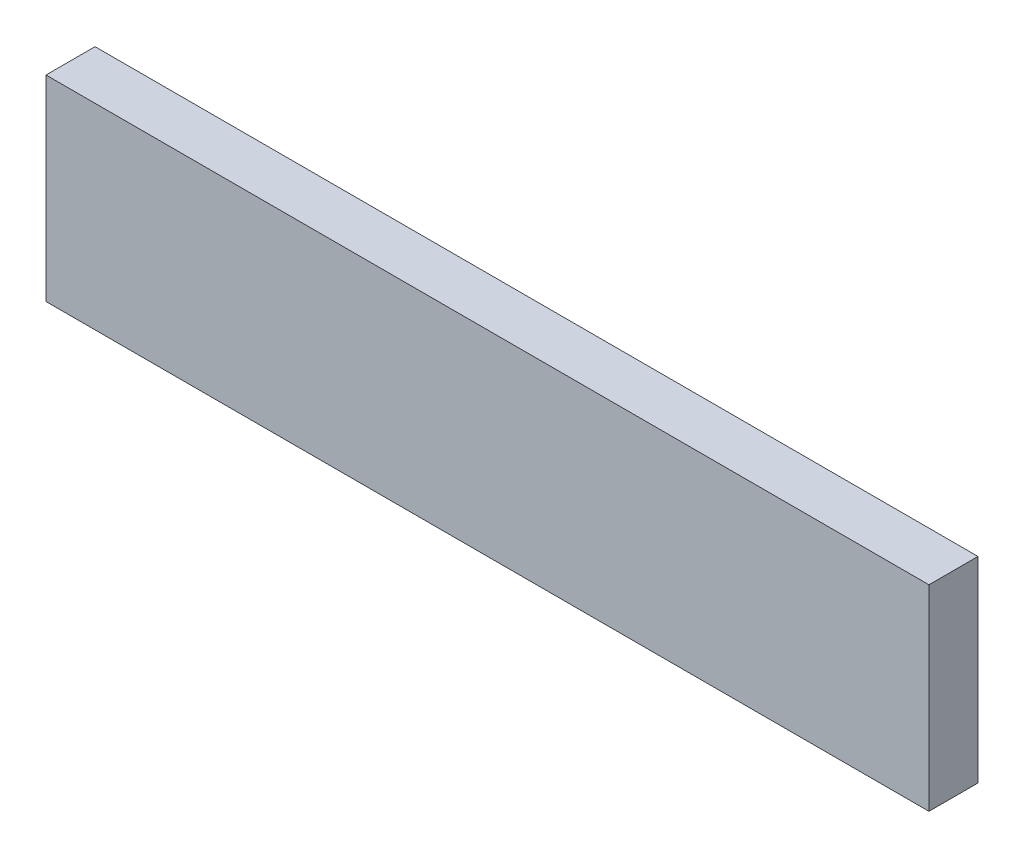
SolidWorks part; units mm, degrees
ref_plane "Plan de face" through (0, 0, 0) normal (0, 0, 1) x (1, 0, 0)
ref_plane "Plan de dessus" through (0, 0, 0) normal (0, 1, 0) x (1, 0, 0)
ref_plane "Plan de droite" through (0, 0, 0) normal (1, 0, 0) x (0, 0, -1)
sketch "Esquisse1" plane through (0, 0, 0) normal (0, 0, 1) x (1, 0, 0)
  line L1 (0, 0) -> (-90, 0)
  line L2 (0, 0) -> (0, 20)
  line L3 (0, 20) -> (-90, 20)
  line L4 (-90, 0) -> (-90, 20)
  dimension "D1" = 90
  dimension "D2" = 20
extrude "Boss.-Extru.1" add sketch "Esquisse1" along normal blind 5
